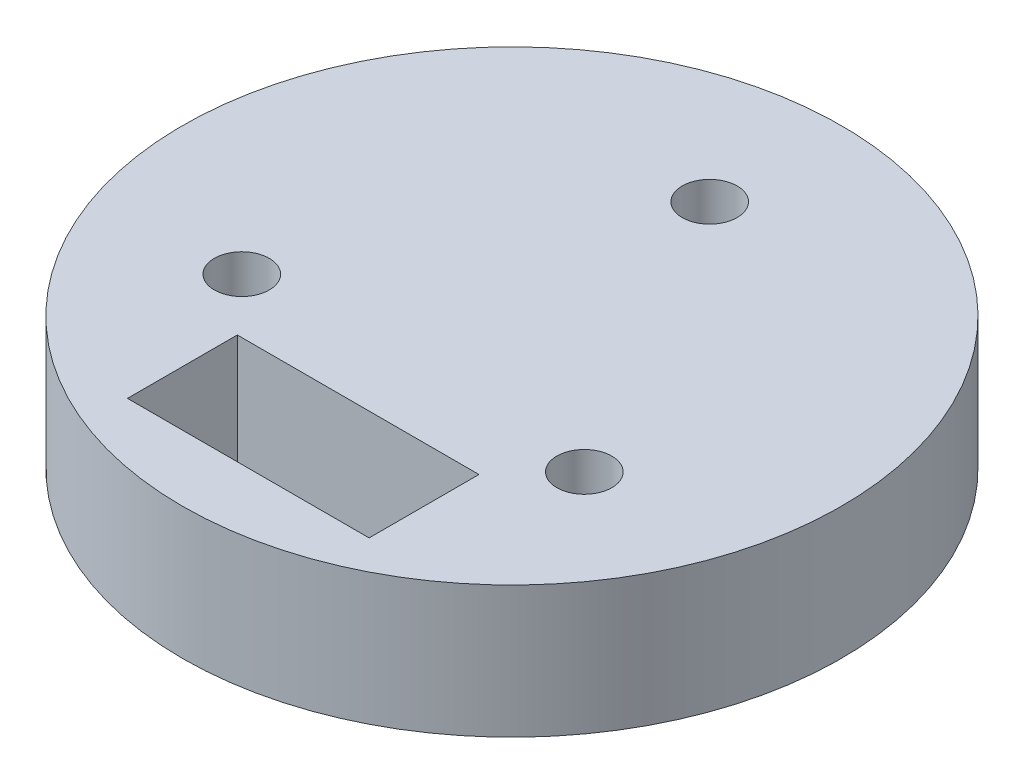
SolidWorks part; units mm, degrees
ref_plane "前视基准面" through (0, 0, 0) normal (0, 0, 1) x (1, 0, 0)
ref_plane "上视基准面" through (0, 0, 0) normal (0, 1, 0) x (1, 0, 0)
ref_plane "右视基准面" through (0, 0, 0) normal (1, 0, 0) x (0, 0, -1)
sketch "草图1" plane through (0, 0, 0) normal (0, 1, 0) x (1, 0, 0)
  line L0 (0, 0) -> (0, 29.3447) construction
  line L1 (0, 0) -> (0, 9) construction
  line L2 (0, 0) -> (0, -24.464) construction
  line L4 (-5.5, -7) -> (5.5, -7)
  line L5 (-5.5, -7) -> (-5.5, -12)
  line L6 (-5.5, -12) -> (5.5, -12)
  line L7 (5.5, -7) -> (5.5, -12)
  circle A0 centre (0, 0) radius 15
  circle A1 centre (0, 0) radius 9 construction
  circle A2 centre (0, 9) radius 1.25
  circle A3 centre (7.7942, -4.5) radius 1.25
  circle A4 centre (-7.7942, -4.5) radius 1.25
  point P5 (0, -24.464)
  point P17 (-21.81, -24.6287)
  point P18 (0, 0)
  point P19 (0, 0)
  point P20 (0, 29.3447)
  point P21 (-86.2145, 22.6203)
  point P22 (-72.3186, 3.7247)
  dimension "D1" = 30
  dimension "D2" = 18
  dimension "D3" = 2.5
  dimension "D6" = 11
  dimension "D7" = 5
  dimension "D8" = 7
  dimension "D4" = 3
extrude "凸台-拉伸1" add sketch "草图1" along normal blind 6
